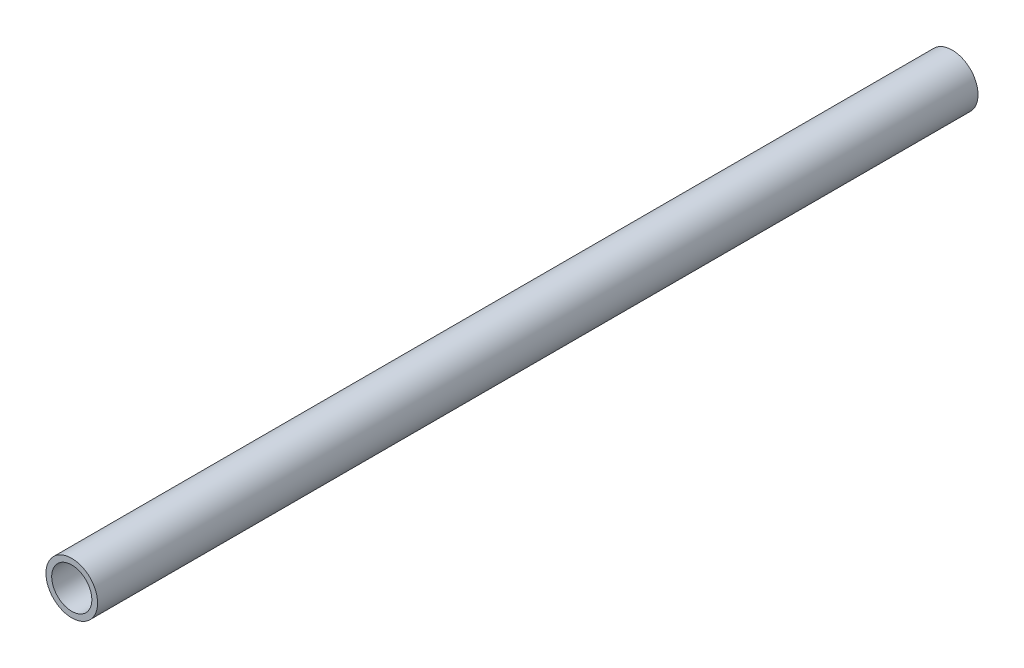
SolidWorks part; units mm, degrees
ref_plane "前视基准面" through (0, 0, 0) normal (0, 0, 1) x (1, 0, 0)
ref_plane "上视基准面" through (0, 0, 0) normal (0, 1, 0) x (1, 0, 0)
ref_plane "右视基准面" through (0, 0, 0) normal (1, 0, 0) x (0, 0, -1)
other "Configuration Table"
sketch "草图1" plane through (0, 0, 0) normal (0, 0, 1) x (1, 0, 0)
  circle A0 centre (0, 0) radius 7
  circle A1 centre (0, 0) radius 9
  dimension "D2" = 14
  dimension "D1" = 2
extrude "凸台-拉伸1" add sketch "草图1" along normal blind 306.9
